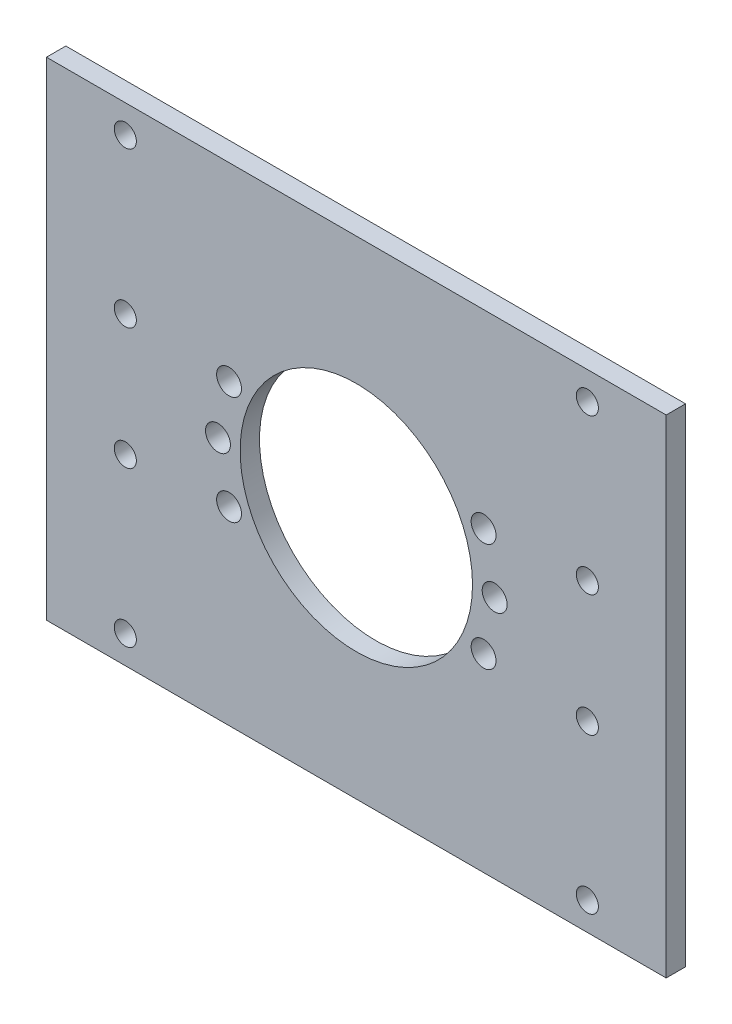
SolidWorks part; units mm, degrees
ref_plane "Front Plane" through (0, 0, 0) normal (0, 0, 1) x (1, 0, 0)
ref_plane "Top Plane" through (0, 0, 0) normal (0, 1, 0) x (1, 0, 0)
ref_plane "Right Plane" through (0, 0, 0) normal (1, 0, 0) x (0, 0, -1)
sketch "Sketch1" plane through (0, 0, 0) normal (0, 0, 1) x (1, 0, 0)
  line L0 (25, 0) -> (23, 9.798)
  line L1 (-21, 0) -> (21, 0) construction
  line L2 (0, 21) -> (0, -21) construction
  line L3 (-56, 25) -> (56, 25)
  line L4 (-56, -44.06) -> (56, -44.06)
  line L5 (-56, -44.06) -> (-56, 44.06)
  line L6 (-56, 44.06) -> (56, 44.06)
  line L7 (56, -44.06) -> (56, 44.06)
  line L8 (-56, -25) -> (56, -25)
  line L9 (0, 0) -> (0, 25) construction
  line L10 (0, 0) -> (0, -25) construction
  line L11 (-25, -25) -> (-25, 25) construction
  line L12 (25, 25) -> (25, -25) construction
  line L13 (0, 25) -> (0, 44.06) construction
  line L14 (0, -25) -> (0, -44.06) construction
  circle A0 centre (0, 0) radius 21
  circle A1 centre (0, 0) radius 25 construction
  circle A2 centre (25, 0) radius 2.25
  circle A3 centre (23, 9.798) radius 2.25
  circle A4 centre (23, -9.798) radius 2.25
  circle A5 centre (-23, 9.798) radius 2.25
  circle A6 centre (-25, 0) radius 2.25
  circle A7 centre (-23, -9.798) radius 2.25
  dimension "D1" = 42
  dimension "D2" = 50
  dimension "D3" = 4.5
  dimension "D5" = 4.5
  dimension "D6" = 88.12
  dimension "D4" = 10
  dimension "D7" = 35
  dimension "D10" = 25
extrude "Boss-Extrude1" add sketch "Sketch1" along normal blind 3.5
sketch "Sketch2" plane through (0, 0, 3.5) normal (0, 0, 1) x (1, 0, 0)
  circle A0 centre (-41.75, 11.0022) radius 1.9978
  circle A1 centre (41.75, 38.9978) radius 1.9978
  circle A2 centre (-41.75, 39.0022) radius 1.9978
  circle A3 centre (41.75, 10.9978) radius 1.9978
  circle A4 centre (41.75, -10.9978) radius 1.9978
  circle A5 centre (41.75, -38.9978) radius 1.9978
  circle A6 centre (-41.75, -38.9978) radius 1.9978
  circle A7 centre (-41.75, -10.9978) radius 1.9978
extrude "Cut-Extrude1" cut sketch "Sketch2" against normal blind 3.5
